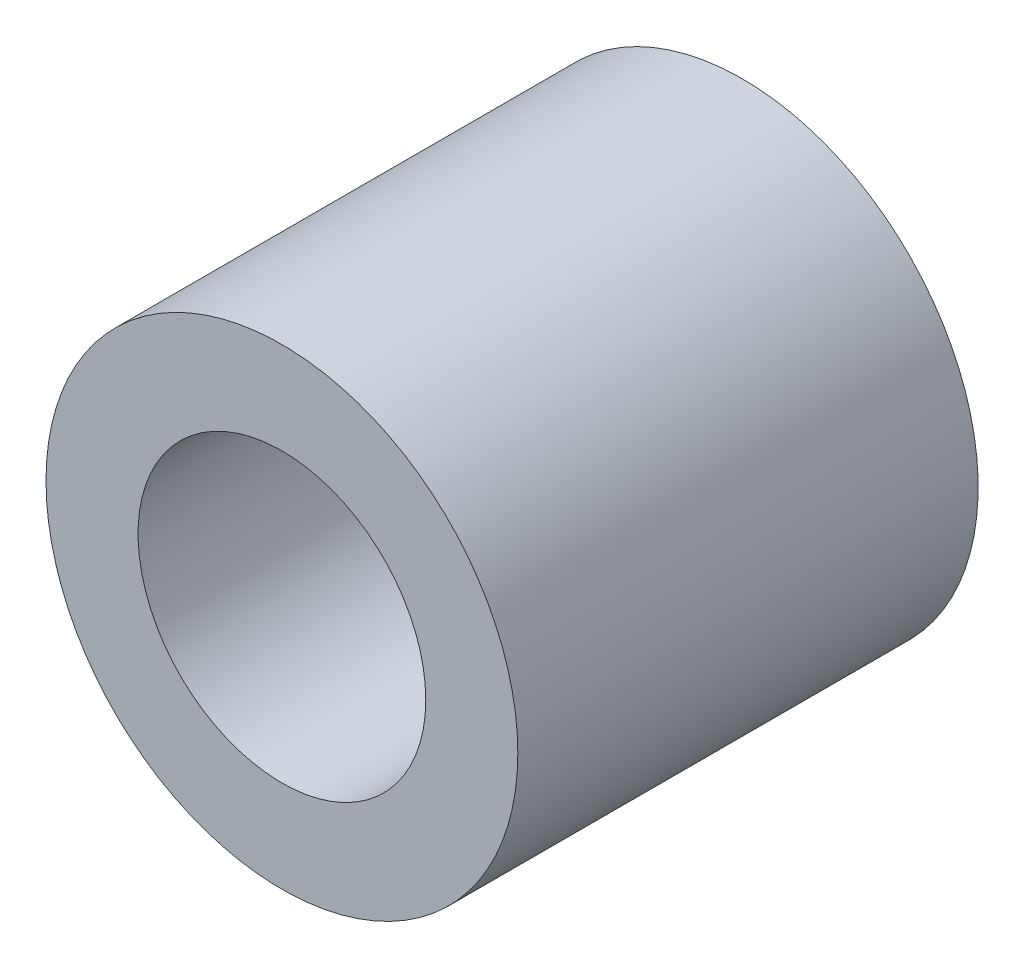
SolidWorks part; units mm, degrees
ref_plane "Alzado" through (0, 0, 0) normal (0, 0, 1) x (1, 0, 0)
ref_plane "Planta" through (0, 0, 0) normal (0, 1, 0) x (1, 0, 0)
ref_plane "Vista lateral" through (0, 0, 0) normal (1, 0, 0) x (0, 0, -1)
sketch "Croquis1" plane through (0, 0, 0) normal (0, 0, 1) x (1, 0, 0)
  circle A0 centre (0, 0) radius 6.25
  circle A1 centre (0, 0) radius 10.25
  dimension "D1" = 12.5
  dimension "D2" = 4
extrude "Saliente-Extruir1" add sketch "Croquis1" along normal blind 10
sketch "Croquis2" plane through (0, 0, 0) normal (0, 0, -1) x (-1, 0, 0)
  circle A1 centre (0, 0) radius 10.25
  circle A2 centre (0, 0) radius 10.25 construction
  circle A3 centre (0, 0) radius 4
  dimension "D1" = 8
extrude "Saliente-Extruir2" add sketch "Croquis2" along normal blind 10
